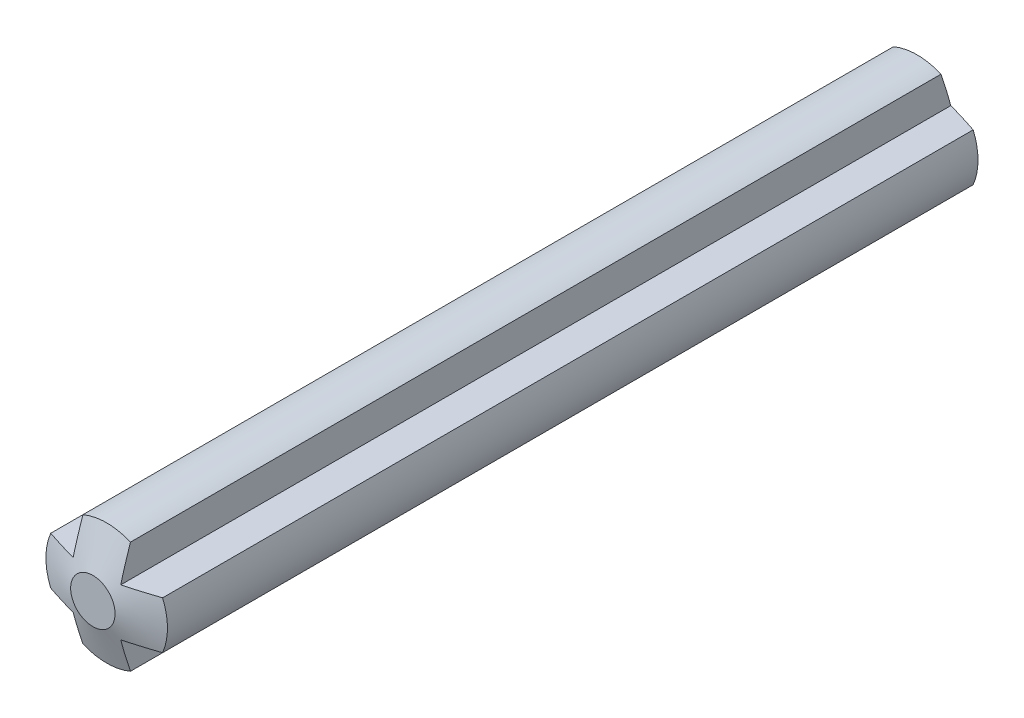
SolidWorks part; units mm, degrees
material "ABS"
ref_plane "Front Plane" through (0, 0, 0) normal (0, 0, 1) x (1, 0, 0)
ref_plane "Top Plane" through (0, 0, 0) normal (0, 1, 0) x (1, 0, 0)
ref_plane "Right Plane" through (0, 0, 0) normal (1, 0, 0) x (0, 0, -1)
sketch "Sketch1" plane through (0, 0, 0) normal (0, 0, 1) x (1, 0, 0)
  line L2 (0, 2.3) -> (0, -2.3) construction
  line L3 (-2.3, 0) -> (2.3, 0) construction
  line L4 (-0.9, 2.1166) -> (-0.9, 0.9)
  line L5 (-2.1166, -0.9) -> (-0.9, -0.9)
  line L12 (0.9, 2.1166) -> (0.9, 0.9)
  line L14 (-2.1166, 0.9) -> (-0.9, 0.9)
  line L15 (0.9, 2.3) -> (0.9, -2.3) construction
  line L17 (-0.9, 2.3) -> (-0.9, -2.3) construction
  line L18 (-2.3, 0.9) -> (2.3, 0.9) construction
  line L19 (-2.3, -0.9) -> (2.3, -0.9) construction
  line L20 (0.9, 0.9) -> (2.1166, 0.9)
  line L21 (0.9, -0.9) -> (0.9, -2.1166)
  line L22 (-0.9, -0.9) -> (-0.9, -2.1166)
  line L23 (0.9, -0.9) -> (2.1166, -0.9)
  arc A9 (0.9, 2.1166) -> (-0.9, 2.1166) centre (0, 0) ccw
  arc A10 (-2.1166, 0.9) -> (-2.1166, -0.9) centre (0, 0) ccw
  arc A11 (-0.9, -2.1166) -> (0.9, -2.1166) centre (0, 0) ccw
  arc A12 (2.1166, -0.9) -> (2.1166, 0.9) centre (0, 0) ccw
  point P28 (0, 0)
  dimension "D1" = 4.6
  dimension "D2" = 0.9
  dimension "D3" = 0.9
extrude "Boss-Extrude1" add sketch "Sketch1" along normal blind 31.72
sketch "Sketch2" plane through (0, 0, 0) normal (0, 1, 0) x (1, 0, 0)
  line L0 (0, 10.1267) -> (0, -37.9071) construction
  line L2 (0.2286, 0.2194) -> (2.8719, 0.2194)
  line L5 (2.8719, 0.2194) -> (2.8719, -0.7282)
  line L6 (2.8719, -0.7282) -> (0.2286, 0.2194)
  line L7 (0, 0) -> (2.8719, 0) construction
  line L14 (2.8719, -30.9918) -> (0.2286, -31.9394)
  line L15 (2.8719, -31.9394) -> (2.8719, -30.9918)
  line L16 (0.2286, -31.9394) -> (2.8719, -31.9394)
  dimension "D1" = 0.2286
  dimension "D2" = 2.8719
  dimension "D3" = 19.721
  dimension "D4" = 19.721
  dimension "D5" = 0.2286
  dimension "D6" = 2.8719
revolve "Cut-Revolve3" cut sketch "Sketch2" angle 360 about L0
equation "\"d_1\"=4.74"
equation "\"tooth_1\"=1.76"
equation "\"h_1\"=1.11"
equation "\"bss_extde\"=31.72"
equation "\"D1@Boss-Extrude1\"=\"bss_extde\""
equation "\"revol_cut_1\"= 30"
